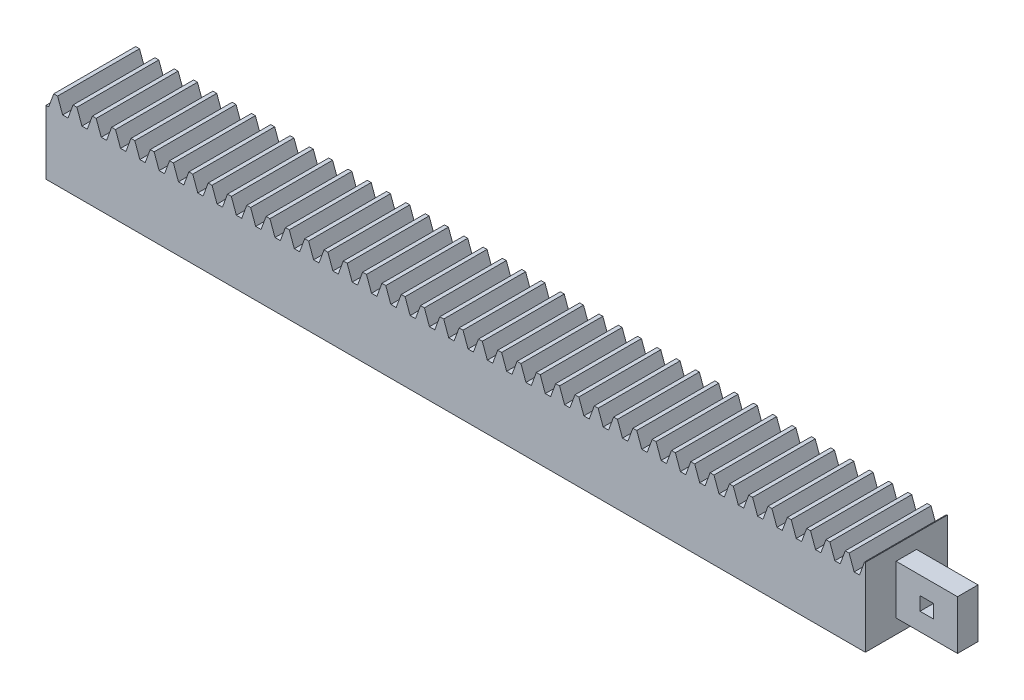
SolidWorks part; units mm, degrees
extrude "Blank" add sketch "BlankSke" against normal blind 20
sketch "BlankSke" plane through (0, 0, 0) normal (0, 0, 1) x (1, 0, 0)
  line L1 (0, 0) -> (200, 0)
  line L2 (0, 0) -> (0, 19)
  line L3 (0, 19) -> (200, 19)
  line L4 (200, 0) -> (200, 19)
  dimension "Length" = 200
  dimension "Blank_height" = 19
ref_plane "Plane1" through (0, 0, 0) normal (0, 0, 1) x (1, 0, 0)
ref_plane "Plane2" through (0, 0, 0) normal (0, 1, 0) x (1, 0, 0)
ref_plane "Plane3" through (0, 0, 0) normal (1, 0, 0) x (0, 0, -1)
other "Configuration Table"
sketch "HoldingSke" plane through (0, 0, 0) normal (0, 1, 0) x (1, 0, 0)
  line L0 (0, 0) -> (0.0928, 0.6602)
  line L1 (-15, 0) -> (100, 0) construction
  line L2 (0, 0) -> (-2.1039, 2.3779)
  line L3 (0, 0) -> (-11.863, 4.5341)
  line L4 (0, 0) -> (6.2122, 5.9991)
  line L5 (0, 0) -> (-23.7986, -8.8762)
  line L6 (0, 0) -> (-10.5278, -7.1032)
  line L9 (-71.009, 38.7566) -> (116.9296, 107.1606)
  line L10 (-76.2, 3.8779) -> (-58.7, 3.8779)
  line L11 (0, 0) -> (-20, 0)
  line L12 (-76.2, 101.6) -> (-76.147, 101.6)
  line L13 (24.9733, 27.94) -> (52.9518, 28.4284)
  line L14 (24.9733, 27.94) -> (24.9743, 27.94)
  line L15 (24.9733, 27.94) -> (100.4006, 29.5858)
  circle A0 centre (0, 0) radius 19.05
  circle A1 centre (0, 0) radius 8.75
  circle A2 centre (0, 0) radius 12.7
  dimension "MPH" = 17.5
  dimension "Diameter" = 38.1
  dimension "Num_teeth" = 44
  dimension "Pitch" = 0.6667
  dimension "Show_teeth" = 998
  dimension "Thickness" = 12.7
  dimension "Ap" = 20
  dimension "Pitch_height" = 17.5
  dimension "Width" = 20
  dimension "Backlash" = 0.053
  dimension "Addendum_fac" = 1
  dimension "Dedendum_fac" = 1.25
  dimension "Clearance_fac" = 0.25
  dimension "Dedendum_add" = 0.001
  dimension "Length" = 200
  dimension "Module" = 1.5
sketch "TooCutSkeIll" plane through (0, 0, 0) normal (0, 0, 1) x (1, 0, 0)
  line L0 (-1.8687, 18.9605) -> (-0.7447, 15.8724)
  line L1 (-0.3914, 15.625) -> (0.3914, 15.625)
  line L2 (0.7447, 15.8724) -> (1.8687, 18.9605)
  line L3 (200, 19) -> (0, 19) construction
  line L4 (0, 0) -> (0, 64.897) construction
  line L5 (-13.208, 17.5) -> (12.954, 17.5) construction
  line L6 (0, 0) -> (200, 0) construction
  line L7 (1.3371, 17.5) -> (1.3371, 48.7463) construction
  line L8 (-1.3371, 17.5) -> (-1.3371, 48.7463) construction
  line L9 (1.9251, 19) -> (1.9251, 19.0254)
  line L10 (-1.9251, 19) -> (-1.9251, 19.0254)
  line L11 (-1.9251, 19.0254) -> (1.9251, 19.0254)
  arc A0 (0.3914, 15.625) -> (0.7447, 15.8724) centre (0.3914, 16.001) ccw
  arc A1 (-0.7447, 15.8724) -> (-0.3914, 15.625) centre (-0.3914, 16.001) ccw
  arc A2 (1.9251, 19) -> (1.8687, 18.9605) centre (1.9251, 18.94) ccw
  arc A3 (-1.8687, 18.9605) -> (-1.9251, 19) centre (-1.9251, 18.94) ccw
  dimension "Pitch_height" = 17.5
  dimension "Addendum_plus" = 1.5254
  dimension "Pressure_angle" = 20
  dimension "Gap_width" = 2.6742
  dimension "Dedendum" = 1.875
extrude "ToothCutIll" [suppressed] cut sketch "TooCutSkeIll" against normal through all
sketch "TooCutSkeSim" plane through (0, 0, 0) normal (0, 0, 1) x (1, 0, 0)
  line L0 (0.6547, 15.625) -> (-0.6547, 15.625)
  line L1 (1.8923, 19.0254) -> (0.6547, 15.625)
  line L2 (0, 17.4625) -> (0, 53.467) construction
  line L3 (1.8923, 19.0254) -> (-1.8923, 19.0254)
  line L6 (-1.8923, 19.0254) -> (-0.6547, 15.625)
  line L9 (-1.3371, 17.5) -> (1.3371, 17.5) construction
  line L10 (0, 0) -> (200, 0) construction
  line L11 (1.3371, 17.5) -> (1.3371, 53.467) construction
  line L12 (-1.3371, 17.5) -> (-1.3371, 53.467) construction
  dimension "Pitch_height" = 17.5
  dimension "Addendum_plus" = 1.5254
  dimension "Pressure_angle" = 20
  dimension "Gap_width" = 2.6742
  dimension "Dedendum" = 1.875
extrude "ToothCutSim" cut sketch "TooCutSkeSim" against normal through all
pattern_linear "TeethCuts" count 43 spacing 4.7124 along (1, 0, 0) of "ToothCutIll", "ToothCutSim"
sketch "Sketch1" plane through (200, 0, 0) normal (1, 0, 0) x (0, 0, -1)
  line L0 (20, 0) -> (0, 0) construction
  line L1 (7.5, 0) -> (12.5, 0)
  line L2 (7.5, 0) -> (7.5, 19)
  line L3 (7.5, 19) -> (12.5, 19)
  line L4 (12.5, 0) -> (12.5, 19)
  line L5 (20, 19) -> (0, 19) construction
  line L8 (0, 0) -> (0, 19) construction
  dimension "D1" = 5
  dimension "D2" = 7.5
extrude "Boss-Extrude1" add sketch "Sketch1" along normal blind 15
sketch "Sketch2" plane through (0, 0, -12.5) normal (0, 0, -1) x (-1, 0, 0)
  line L0 (-200, 0) -> (-200, 19) construction
  line L1 (-215, 19) -> (-200, 19)
  line L2 (-215, 19) -> (-215, 15.5)
  line L3 (-215, 15.5) -> (-200, 15.5)
  line L4 (-200, 19) -> (-200, 15.5)
  line L5 (-200, 0) -> (-200, 19) construction
  line L6 (-215, 0) -> (-200, 0)
  line L7 (-215, 0) -> (-215, 3.5)
  line L8 (-215, 3.5) -> (-200, 3.5)
  line L9 (-200, 0) -> (-200, 3.5)
  line L10 (-215, 3.5) -> (-200, 15.5) construction
  line L11 (-200, 3.5) -> (-215, 15.5) construction
  line L13 (-209.15, 11.15) -> (-205.85, 11.15)
  line L14 (-209.15, 11.15) -> (-209.15, 7.85)
  line L15 (-209.15, 7.85) -> (-205.85, 7.85)
  line L16 (-205.85, 11.15) -> (-205.85, 7.85)
  line L17 (-209.15, 11.15) -> (-205.85, 7.85) construction
  line L18 (-209.15, 7.85) -> (-205.85, 11.15) construction
  point P14 (-207.5, 9.5)
  dimension "D3" = 3.3
  dimension "D1" = 3.5
  dimension "D2" = 3.5
  dimension "D4" = 3.3
extrude "Cut-Extrude1" cut sketch "Sketch2" against normal up to surface (5 mm away) up to face at (207.5, 9.5, -7.5)
equation "' \"Module@HoldingSke\" = 6.35"
equation "' \"Num_teeth@HoldingSke\" = 12"
equation "' \"Ap@HoldingSke\" =  20"
equation "' \"Ap@HoldingSke\" = 20"
equation "' \"Width@HoldingSke\" = 0.25 * 25.4"
equation "' \"Show_teeth@HoldingSke\" = 500"
equation "' \"Backlash@HoldingSke\" = 0.009 * 25.4"
equation "' \"Addendum_fac@HoldingSke\" = 1.0"
equation "' \"Dedendum_fac@HoldingSke\" = 1.25"
equation "' \"Dedendum_add@HoldingSke\" = 0.00005 * 25.4"
equation "' \"Clearance_fac@HoldingSke\" = 0.25"
equation "' \"Pitch_height@HoldingSke\" = 1 * 25.4"
equation "' \"Length@HoldingSke\" = 4.71 * 25.4"
equation "\"Pitch@HoldingSke\" = 1 / \"Module@HoldingSke\""
equation "\"MPH@HoldingSke\" = \"Dedendum_fac@HoldingSke\" / \"Pitch@HoldingSke\" + 2 * \"Dedendum_add@HoldingSke\" + 0.002 * 25.4"
equation "\"MPH@HoldingSke\" = ((sgn( \"MPH@HoldingSke\" - \"Pitch_height@HoldingSke\")+1)*( \"MPH@HoldingSke\" - \"Pitch_height@HoldingSke\"))/2 + \"Pitch_height@HoldingSke\""
equation "\"Blank_height@BlankSke\" = \"Pitch_height@HoldingSke\" + \"Addendum_fac@HoldingSke\"  / \"Pitch@HoldingSke\" "
equation "\"Length@BlankSke\" =  \"Length@HoldingSke\""
equation "\"Face_width@Blank\" = \"Width@HoldingSke\""
equation "\"Pressure_angle@TooCutSkeIll\" = \"Ap@HoldingSke\""
equation "\"Addendum_plus@TooCutSkeIll\" =  \"Addendum_fac@HoldingSke\"  / \"Pitch@HoldingSke\" + 0.001 *25.4"
equation "\"Dedendum@TooCutSkeIll\" = \"Dedendum_fac@HoldingSke\"  / \"Pitch@HoldingSke\""
equation "\"Pitch_height@TooCutSkeIll\" =  \"MPH@HoldingSke\""
equation "\"Gap_width@TooCutSkeIll\" = 3.14159265 / 2 / \"Pitch@HoldingSke\" + 6 * \"Backlash@HoldingSke\""
equation "\"Pressure_angle@TooCutSkeSim\" = \"Ap@HoldingSke\""
equation "\"Addendum_plus@TooCutSkeSim\" =  \"Addendum_fac@HoldingSke\"  / \"Pitch@HoldingSke\" + 0.001 * 25.4"
equation "\"Dedendum@TooCutSkeSim\" = \"Dedendum_fac@HoldingSke\"  / \"Pitch@HoldingSke\""
equation "\"Pitch_height@TooCutSkeSim\" =  \"MPH@HoldingSke\""
equation "\"Gap_width@TooCutSkeSim\" = 3.14159265 / 2 / \"Pitch@HoldingSke\" + 6 * \"Backlash@HoldingSke\""
equation "\"Root_fillet@TooCutSkeIll\" = \"Clearance_fac@HoldingSke\" / \"Pitch@HoldingSke\" + \"Dedendum_add@HoldingSke\""
equation "\"Break_rad@TooCutSkeIll\" = 0.02 / \"Pitch@HoldingSke\" * 2"
equation "\"Linear_pitch@TeethCuts\" = 3.14159265 / \"Pitch@HoldingSke\""
equation "\"Num_teeth@HoldingSke\" = int( ( \"Length@HoldingSke\" + 0 ) / (3.14159265 / \"Pitch@HoldingSke\")) + 0.9999  + 1"
equation " \"Num_teeth@TeethCuts\" = int( \"Show_teeth@HoldingSke\" ) + 1"
equation " \"Num_teeth@TeethCuts\" = ((sgn( \"Num_teeth@TeethCuts\" - \"Num_teeth@HoldingSke\" )-1)*( \"Num_teeth@TeethCuts\" - \"Num_teeth@HoldingSke\" ))/-2+ \"Num_teeth@HoldingSke\""
equation " \"Num_teeth@TeethCuts\" = ((sgn( \"Num_teeth@TeethCuts\" - 2.0)+1)*( \"Num_teeth@TeethCuts\" - 2.0))/2 +2.0"
